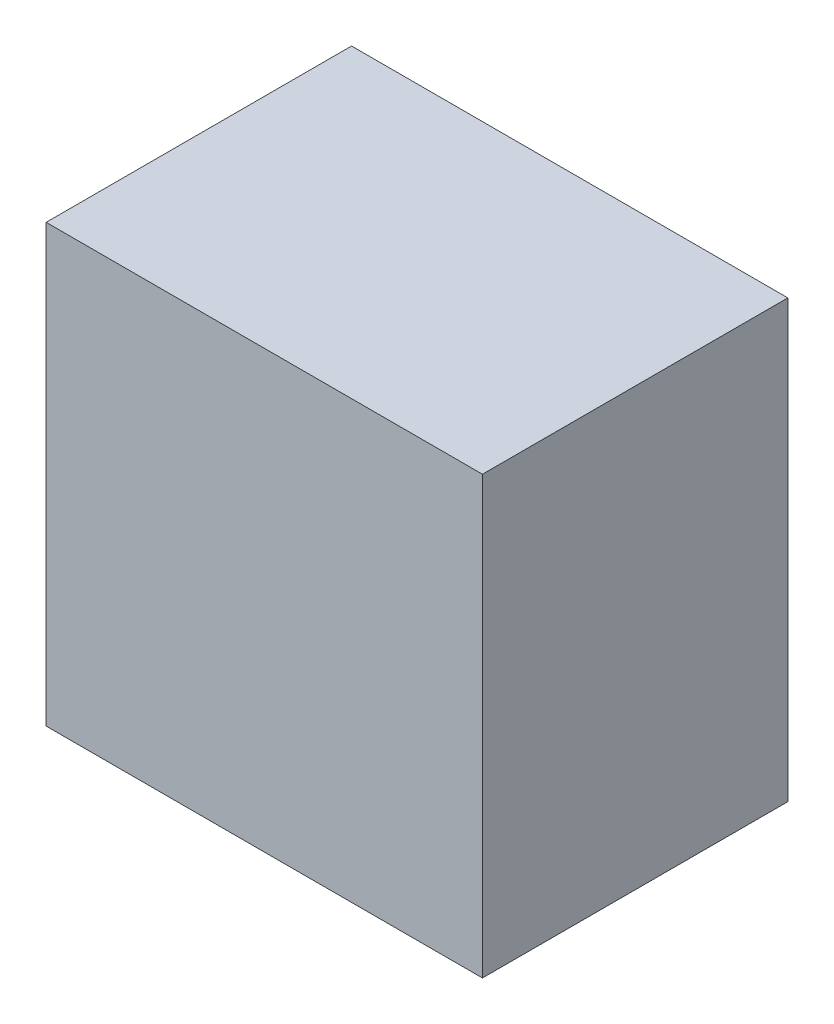
SolidWorks part; units mm, degrees
material "ABS"
ref_plane "前视基准面" through (0, 0, 0) normal (0, 0, 1) x (1, 0, 0)
ref_plane "上视基准面" through (0, 0, 0) normal (0, 1, 0) x (1, 0, 0)
ref_plane "右视基准面" through (0, 0, 0) normal (1, 0, 0) x (0, 0, -1)
other "Configuration Table"
sketch "草图1" plane through (0, 0, 0) normal (0, 0, 1) x (1, 0, 0)
  line L0 (-11.8425, 0) -> (2.7756, 0) construction
  line L1 (0, 5.077) -> (0, -4.1056) construction
  line L3 (-5, -5) -> (5, -5)
  line L4 (-5, -5) -> (-5, 5)
  line L5 (-5, 5) -> (5, 5)
  line L6 (5, -5) -> (5, 5)
  line L7 (-5, -5) -> (5, 5) construction
  line L8 (-5, 5) -> (5, -5) construction
  point P4 (0, 0)
  dimension "D2" = 10
extrude "凸台-拉伸1" add sketch "草图1" along normal blind 7
